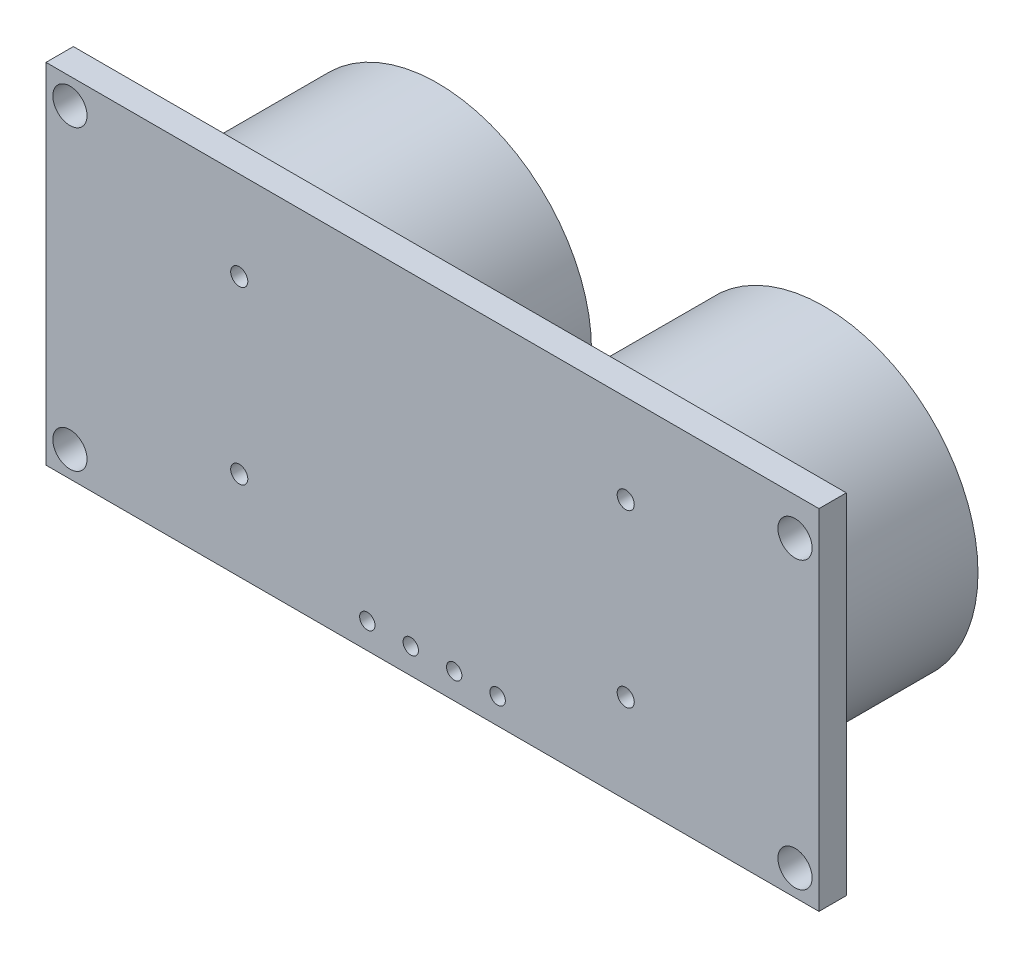
SolidWorks part; units mm, degrees
ref_plane "Спереди" through (0, 0, 0) normal (0, 0, 1) x (1, 0, 0)
ref_plane "Сверху" through (0, 0, 0) normal (0, 1, 0) x (1, 0, 0)
ref_plane "Справа" through (0, 0, 0) normal (1, 0, 0) x (0, 0, -1)
sketch "Эскиз1" plane through (0, 0, 0) normal (0, 0, 1) x (1, 0, 0)
  line L1 (22.6, -10.2) -> (-22.6, -10.2)
  line L2 (22.6, -10.2) -> (22.6, 10.2)
  line L3 (22.6, 10.2) -> (-22.6, 10.2)
  line L4 (-22.6, -10.2) -> (-22.6, 10.2)
  line L5 (22.6, -10.2) -> (-22.6, 10.2) construction
  line L6 (22.6, 10.2) -> (-22.6, -10.2) construction
  point P0 (0, 0)
  dimension "D1" = 45.2
  dimension "D2" = 20.4
extrude "Бобышка-Вытянуть1" add sketch "Эскиз1" along normal blind 1.6
sketch "Эскиз2" plane through (0, 0, 1.6) normal (0, 0, 1) x (1, 0, 0)
  line L0 (0, 10.2) -> (0, -10.2) construction
  line L1 (22.6, 10.2) -> (-22.6, 10.2) construction
  line L2 (-22.6, -10.2) -> (22.6, -10.2) construction
  line L3 (-22.6, 0) -> (22.6, 0) construction
  line L4 (-22.6, 10.2) -> (-22.6, -10.2) construction
  line L5 (22.6, -10.2) -> (22.6, 10.2) construction
  line L6 (-21.2, 0) -> (-21.2, 8.7) construction
  line L7 (-21.2, -8.7) -> (-21.2, 0) construction
  line L8 (21.2, -8.7) -> (21.2, 0) construction
  line L9 (21.2, 8.7) -> (21.2, 0) construction
  line L10 (-21.2, 8) -> (0, 8) construction
  line L11 (0, 8) -> (21.2, 8) construction
  line L12 (-21.2, -8.7) -> (20.9706, -8.7) construction
  circle A0 centre (-21.2, 8.7) radius 1
  circle A1 centre (-21.2, -8.7) radius 1
  circle A2 centre (21.2, -8.7) radius 1
  circle A3 centre (21.2, 8) radius 1
  circle A4 centre (-3.81, -8.7) radius 0.45
  circle A5 centre (-1.27, -8.7) radius 0.45
  circle A6 centre (1.27, -8.7) radius 0.45
  circle A7 centre (3.81, -8.7) radius 0.45
  point P34 (0, 0)
  point P35 (0, 0)
  point P36 (0, 0)
  dimension "D4" = 2
  dimension "D9" = 0.9
  dimension "D1" = 42.4
  dimension "D2" = 17.4
  dimension "D3" = 8
  dimension "D5" = 2.54
  dimension "D6" = 1.27
  dimension "D7" = 2.54
  dimension "D8" = 2.54
extrude "Вырез-Вытянуть1" cut sketch "Эскиз2" against normal through all
sketch "Эскиз3" plane through (0, 0, 1.6) normal (0, 0, 1) x (1, 0, 0)
  line L0 (0, 10.2) -> (0, -10.2) construction
  line L1 (22.6, 10.2) -> (-22.6, 10.2) construction
  line L2 (-22.6, -10.2) -> (22.6, -10.2) construction
  line L3 (22.6, 0) -> (0, 0) construction
  line L4 (22.6, -10.2) -> (22.6, 10.2) construction
  line L5 (11.3, 0) -> (11.3, 5) construction
  line L6 (11.3, 0) -> (11.3, -5) construction
  circle A0 centre (11.3, 5) radius 0.5
  circle A1 centre (11.3, -5) radius 0.5
  circle A2 centre (-11.3, -5) radius 0.5
  circle A3 centre (-11.3, 5) radius 0.5
  dimension "D1" = 1
  dimension "D2" = 10
extrude "Вырез-Вытянуть2" cut sketch "Эскиз3" against normal through all
sketch "Эскиз4" plane through (0, 0, 0) normal (0, 0, -1) x (-1, 0, 0)
  line L0 (0, 10.2) -> (0, -10.2) construction
  line L1 (-22.6, 10.2) -> (22.6, 10.2) construction
  line L2 (22.6, -10.2) -> (-22.6, -10.2) construction
  line L3 (-22.6, 0) -> (0, 0) construction
  line L4 (-22.6, -10.2) -> (-22.6, 10.2) construction
  line L5 (-11.3, 5) -> (-11.3, -5) construction
  circle A0 centre (-11.3, 0) radius 9
  circle A1 centre (11.3, 0) radius 9
  dimension "D1" = 18
extrude "Бобышка-Вытянуть2" add sketch "Эскиз4" along normal blind 10
